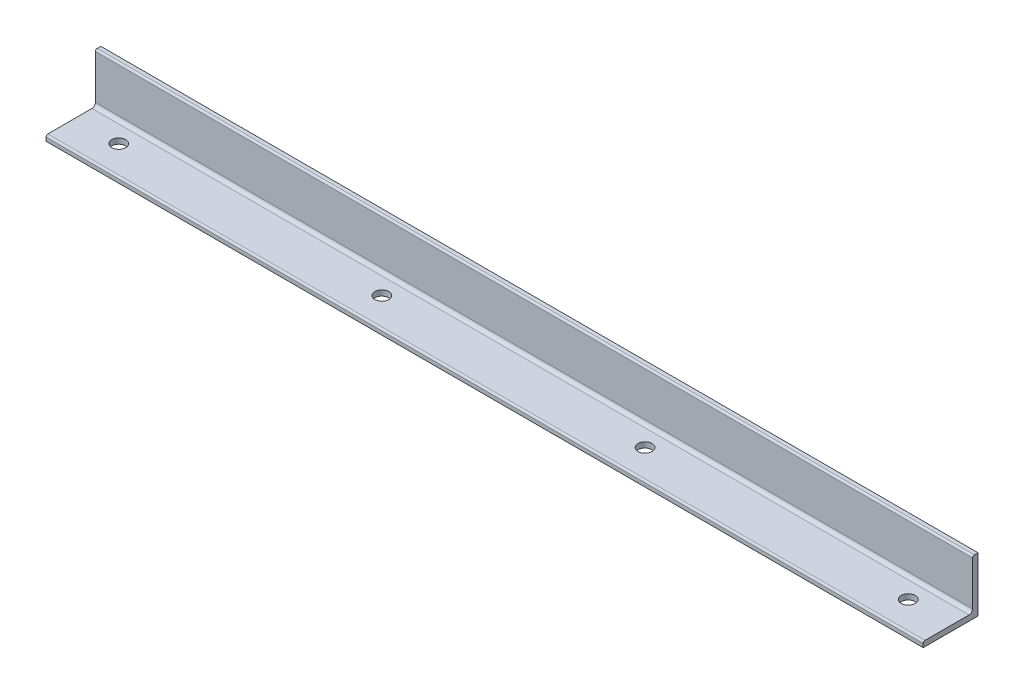
SolidWorks part; units mm, degrees
material "ASTM A36 Steel"
ref_plane "Front Plane" through (0, 0, 0) normal (0, 0, 1) x (1, 0, 0)
ref_plane "Top Plane" through (0, 0, 0) normal (0, 1, 0) x (1, 0, 0)
ref_plane "Right Plane" through (0, 0, 0) normal (1, 0, 0) x (0, 0, -1)
sketch "Sketch6" plane through (0, 0, 0) normal (1, 0, 0) x (0, 0, -1)
  line L0 (17.0434, 0) -> (32.9184, 0)
  line L1 (32.9184, 0) -> (32.9184, 15.875)
  line L2 (32.9184, 15.875) -> (31.8516, 15.875)
  line L3 (31.3436, 15.367) -> (31.3436, 2.5908)
  line L4 (30.3276, 1.5748) -> (17.5514, 1.5748)
  line L5 (17.0434, 1.0668) -> (17.0434, 0)
  arc A0 (31.3436, 2.5908) -> (30.3276, 1.5748) centre (30.3276, 2.5908) cw
  arc A1 (17.5514, 1.5748) -> (17.0434, 1.0668) centre (17.5514, 1.0668) ccw
  arc A2 (31.8516, 15.875) -> (31.3436, 15.367) centre (31.8516, 15.367) ccw
  dimension "D1" = 1.016
  dimension "D2" = 0.508
  dimension "D3" = 1.5748
  dimension "D4" = 1.5748
  dimension "D5" = 15.875
  dimension "D6" = 15.875
  dimension "D7" = 32.9184
extrude "Boss-Extrude1" add sketch "Sketch6" against normal blind 254
sketch "Sketch3" plane through (0, 0, 0) normal (0, 1, 0) x (1, 0, 0)
  line L0 (-33.0377, 0) -> (-104.4903, 0) construction
  line L1 (-254, 17.0434) -> (-254, 32.9184) construction
  circle A0 centre (-12.7, 25.4) radius 2.0193
  circle A1 centre (-88.9, 25.4) radius 2.0193
  circle A2 centre (-165.1, 25.4) radius 2.0193
  circle A3 centre (-241.3, 25.4) radius 2.0193
  dimension "D2" = 76.2
  dimension "D3" = 12.7
  dimension "D4" = 4.0386
  dimension "D5" = 25.4
  dimension "D6" = 12.7
  dimension "D7" = 76.2
  dimension "D1" = 76.2
extrude "Cut-Extrude1" cut sketch "Sketch3" along normal through all
